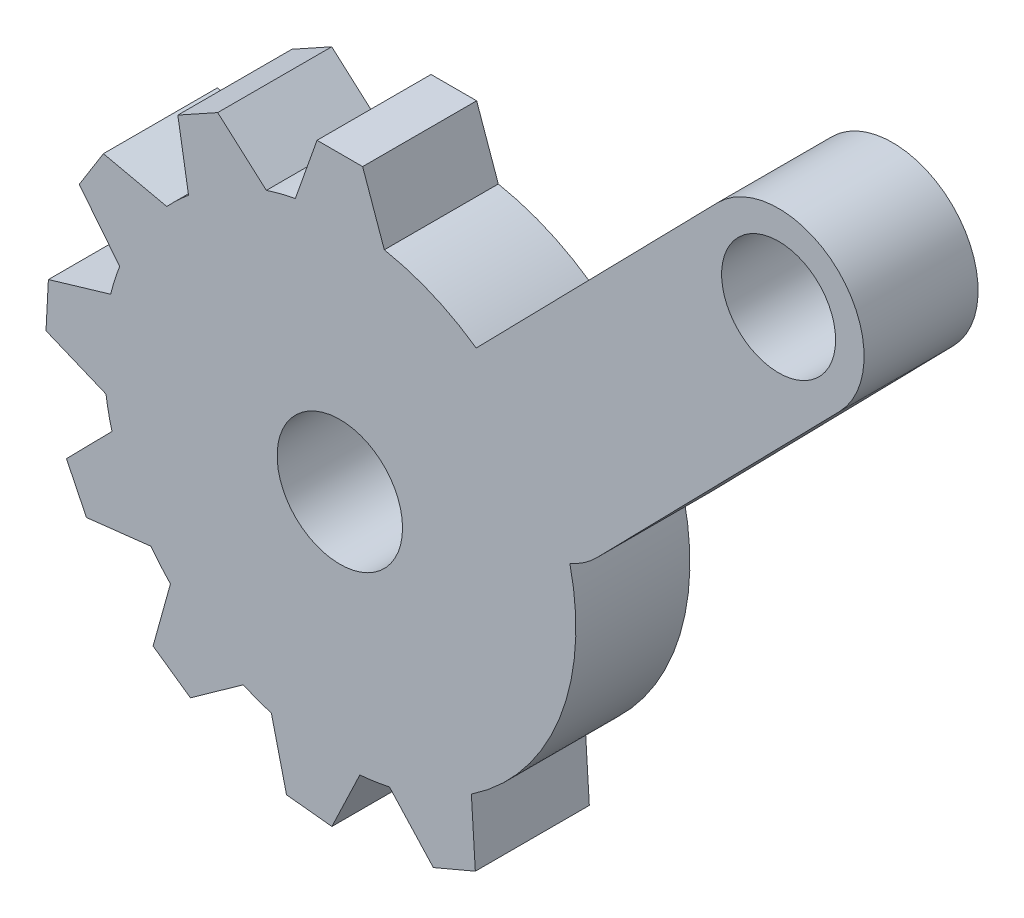
SolidWorks part; units mm, degrees
ref_plane "Alzado" through (0, 0, 0) normal (0, 0, 1) x (1, 0, 0)
ref_plane "Planta" through (0, 0, 0) normal (0, 1, 0) x (1, 0, 0)
ref_plane "Vista lateral" through (0, 0, 0) normal (1, 0, 0) x (0, 0, -1)
sketch "Croquis1" plane through (0, 0, 0) normal (0, 0, 1) x (1, 0, 0)
  line L4 (-2, 25.7064) -> (-3.9017, 20.3355)
  line L5 (2, 25.7064) -> (3.9017, 20.3355)
  line L6 (-2, 25.7064) -> (2, 25.7064)
  arc A0 (-3.9017, 20.3355) -> (3.9017, 20.3355) centre (0, 0) ccw
  circle A1 centre (0, 0) radius 5
  dimension "D1" = 10
extrude "Saliente-Extruir5" add sketch "Croquis1" along normal blind 10
pattern_circular "MatrizC4" count 8 every 29 about axis through (0, 0, 0) along (0, 0, 1) of "Saliente-Extruir5"
sketch "Croquis9" plane through (0, 0, 10) normal (0, 0, 1) x (1, 0, 0)
  line L0 (14.7406, 19.7406) -> (34.821, 39.821) construction
  line L1 (34.8506, 29.8506) -> (43.6869, 38.6869) construction
  line L2 (17.1989, 11.5305) -> (38.4897, 33.2795) construction
  line L4 (11.8394, 16.777) -> (33.1302, 38.5261)
  line L5 (22.5584, 6.2839) -> (43.8491, 28.033)
  arc A1 (11.5372, -17.1944) -> (3.9017, 20.3355) centre (0, 0) ccw construction
  arc A2 (11.8394, 16.777) -> (22.5584, 6.2839) centre (17.1989, 11.5305) ccw
  arc A3 (43.8491, 28.033) -> (33.1302, 38.5261) centre (38.4897, 33.2795) ccw
  circle A4 centre (38.4897, 33.2795) radius 5
  point P13 (27.8443, 22.405)
extrude "Saliente-Extruir6" add sketch "Croquis9" against normal blind 10
sketch "Croquis11" plane through (0, 0, 10) normal (0, 0, 1) x (1, 0, 0)
  circle A0 centre (0, 0) radius 5
extrude "Saliente-Extruir7" add sketch "Croquis11" against normal blind 10
sketch "Croquis12" plane through (0, 0, 10) normal (0, 0, 1) x (1, 0, 0)
  arc A0 (-3.7712, 4.6667) -> (3.7712, 4.6667) centre (0, 0) ccw
  arc A1 (3.7712, 4.6667) -> (-3.7712, 4.6667) centre (0, 6) ccw
extrude "Cortar-Extruir2" cut sketch "Croquis12" against normal blind 10
sketch "Croquis13" plane through (0, 0, 10) normal (0, 0, 1) x (1, 0, 0)
  arc A0 (3.7712, 4.6667) -> (-3.7712, 4.6667) centre (0, 6) ccw
  arc A1 (-3.7712, 4.6667) -> (3.7712, 4.6667) centre (0, 0) ccw
extrude "Saliente-Extruir9" add sketch "Croquis13" against normal blind 10
sketch "Croquis15" plane through (0, 0, 10) normal (0, 0, 1) x (1, 0, 0)
  circle A0 centre (0, 0) radius 6
extrude "Cortar-Extruir4" cut sketch "Croquis15" against normal blind 10
scale "Escala1" bodies to scale 121 scale about centroid uniform scaling yes scale factor 0.75
sketch "Croquis16" plane through (0, 0, 8.75) normal (0, 0, 1) x (1, 0, 0)
  circle A0 centre (1.4193, 1.324) radius 4.5
  circle A1 centre (1.4193, 1.324) radius 4.125
extrude "Saliente-Extruir12" add sketch "Croquis16" against normal blind 7.5 contours A0 | A1
